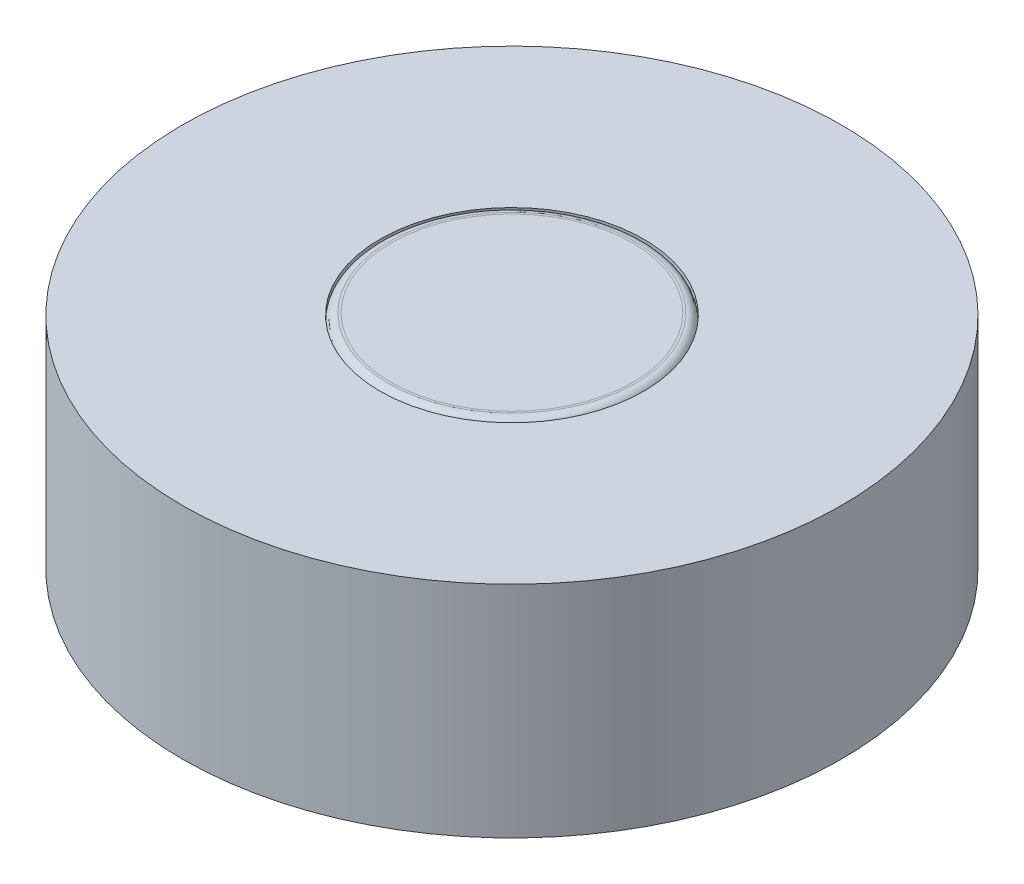
SolidWorks part; units mm, degrees
ref_plane "Front Plane" through (0, 0, 0) normal (0, 0, 1) x (1, 0, 0)
ref_plane "Top Plane" through (0, 0, 0) normal (0, 1, 0) x (1, 0, 0)
ref_plane "Right Plane" through (0, 0, 0) normal (1, 0, 0) x (0, 0, -1)
sketch "Sketch1" plane through (0, 0, 0) normal (0, 1, 0) x (1, 0, 0)
  circle A0 centre (0, 0) radius 15
  circle A1 centre (0, 0) radius 6
extrude "Boss-Extrude1" add sketch "Sketch1" along normal blind 10
sketch "Sketch2" plane through (0, 0, 0) normal (0, 1, 0) x (1, 0, 0)
  circle A0 centre (0, 0) radius 6
  circle A1 centre (0, 0) radius 5.5
extrude "Boss-Extrude2" add sketch "Sketch2" along normal blind 10.1 separate body
fillet "Fillet1" radius 0.4 1 edges at (0, 10.1, 6)
ref_plane "Plane1" through (0, 10, 0) normal (0, 1, 0) x (1, 0, 0)
sketch "Sketch3" plane through (0, 10, 0) normal (0, 1, 0) x (1, 0, 0)
  circle A0 centre (0, 0) radius 5.5
extrude "Boss-Extrude3" add sketch "Sketch3" along normal blind 0.1 separate body
